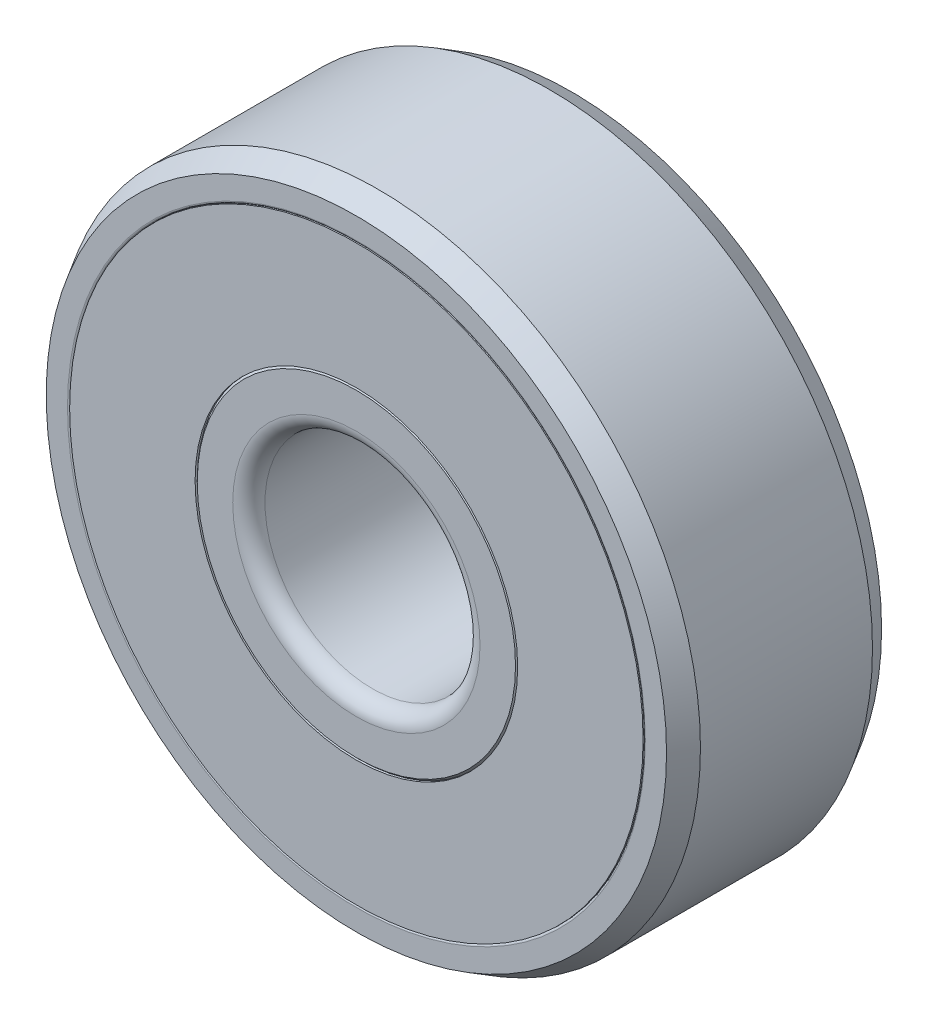
SolidWorks part; units mm, degrees
ref_plane "Front Plane" through (0, 0, 0) normal (0, 0, 1) x (1, 0, 0)
ref_plane "Top Plane" through (0, 0, 0) normal (0, 1, 0) x (1, 0, 0)
ref_plane "Right Plane" through (0, 0, 0) normal (1, 0, 0) x (0, 0, -1)
sketch "Sketch1" plane through (0, 0, 0) normal (0, 0, 1) x (1, 0, 0)
  line L0 (0, 4) -> (0, 6) construction
  line L1 (0, 2) -> (0, 4) construction
  line L2 (0, 6) -> (0, 5.3333) construction
  line L3 (0, 5.3333) -> (0, 4.6667) construction
  line L4 (0, 4.6667) -> (0, 4) construction
  circle A0 centre (0, 0) radius 2
  circle A1 centre (0, 0) radius 6
  circle A2 centre (0, 0) radius 5.3333 construction
  circle A4 centre (0, 0) radius 3 construction
  point P6 (0, 3)
  dimension "OD" = 12
  dimension "ID" = 4
sketch "Sketch2" plane through (0, 0, 0) normal (1, 0, 0) x (0, 0, -1)
  line L0 (-2, 6) -> (2, 6) construction
  line L1 (2, 6) -> (2, -6) construction
  line L2 (2, 0) -> (-2, 0) construction
  line L3 (-2, 2) -> (-2, -2) construction
  point P2 (0, 6)
  dimension "Width" = 4
  dimension "For Shaft Diameter" = 4
  dimension "For Housing ID" = 12
sketch "Sketch3" plane through (0, 0, 0) normal (1, 0, 0) x (0, 0, -1)
  line L0 (-1.6, -6) -> (1.6, -6)
  line L3 (-2, -5.3733) -> (-2, -5.7691)
  line L4 (0, -3) -> (0, -5.3333) construction
  line L5 (-1.6, -6) -> (-2, -5.7691)
  line L6 (-1.7, -2) -> (1.7, -2)
  line L7 (-1.1111, -5.3333) -> (-1.1111, -5.5556) construction
  line L8 (-1.96, -3) -> (-1.1111, -3)
  line L9 (-2, -3) -> (0, -3) construction
  line L11 (-2, -5.3333) -> (-2, -3) construction
  line L12 (-2, -2.96) -> (-2, -2.3)
  line L14 (-2, 0) -> (2, 0) construction
  line L15 (-1.96, -5.3333) -> (-1.1111, -5.3333)
  line L17 (0, 0) -> (0, -6) construction
  line L18 (-1.1111, -5.5556) -> (-1.1111, -5.7778) construction
  line L19 (1.6, -6) -> (2, -5.7691)
  line L20 (0, -5.3333) -> (-2, -5.3333) construction
  line L21 (-2, 2) -> (-2, -2) construction
  line L22 (-1.1111, -5.7778) -> (-1.1111, -6) construction
  line L30 (-2, -2.96) -> (-1.96, -3)
  line L31 (1.96, -3) -> (1.1111, -3)
  line L32 (2, -2.96) -> (1.96, -3)
  line L33 (2, -2.96) -> (2, -2.3)
  line L34 (1.96, -5.3333) -> (1.1111, -5.3333)
  line L35 (2, -5.3733) -> (2, -5.7691)
  line L36 (0, 6) -> (0, -6) construction
  arc A0 (0, -2.5556) -> (0, -5.7778) centre (0, -4.1667) ccw construction
  arc A1 (-1.1111, -3) -> (1.1111, -3) centre (0, -4.1667) cw
  arc A2 (-1.1111, -5.3333) -> (1.1111, -5.3333) centre (0, -4.1667) ccw
  arc A4 (-1.96, -5.3333) -> (-2, -5.3733) centre (-1.96, -5.3733) ccw
  arc A5 (-1.7, -2) -> (-2, -2.3) centre (-1.7, -2.3) ccw
  arc A6 (1.7, -2) -> (2, -2.3) centre (1.7, -2.3) cw
  arc A7 (1.96, -5.3333) -> (2, -5.3733) centre (1.96, -5.3733) cw
  point P28 (0, -4.1667)
  point P46 (-2, -2)
  point P54 (0, -2)
  dimension "D4" = 0.04
  dimension "D7" = 0.3
  dimension "D5" = 45
  dimension "D6" = 0.04
  dimension "D3" = 0.4
  dimension "D2" = 60
revolve "Revolve1" add sketch "Sketch3" angle 360 about L14
sketch "Sketch4" plane through (0, 0, 0) normal (1, 0, 0) x (0, 0, -1)
  line L0 (-1.96, -5.3333) -> (-1.1111, -5.3333) construction
  line L1 (-2, -3) -> (-1.7083, -3)
  line L2 (-2, -3) -> (-2, -5.3333)
  line L3 (-2, -5.3333) -> (-1.7083, -5.3333)
  line L4 (-1.7083, -3) -> (-1.7083, -5.3333)
  line L5 (-2, -2.96) -> (-2, -2.3) construction
  line L6 (-2, -4.1667) -> (-1.9028, -4.1667) construction
  line L7 (-1.9028, -4.1667) -> (-1.8056, -4.1667) construction
  line L8 (-1.8056, -4.1667) -> (-1.7083, -4.1667) construction
  line L9 (-1.7083, -4.1667) -> (-1.6111, -4.1667) construction
  line L10 (-2, -5.3333) -> (-2, -3) construction
  line L11 (-1.96, -3) -> (-1.1111, -3) construction
  arc A1 (0, -2.5556) -> (0, -5.7778) centre (0, -4.1667) ccw construction
revolve "Revolve2" add sketch "Sketch4" angle 360 about L14
sketch "Sketch5" plane through (0, 0, 0) normal (1, 0, 0) x (0, 0, -1)
  line L2 (0, -2.5556) -> (0, -5.7778)
  arc A2 (0, -5.7778) -> (0, -2.5556) centre (0, -4.1667) cw
revolve "Revolve3" add sketch "Sketch5" angle 360 about L17
pattern_circular "CirPattern1" count 7 over 360 about axis through (0, 0, 0) along (0, 0, 1) of bodies 138
equation "\"D4@Sketch3\"=\"Width@Sketch2\"*.01"
equation "\"D6@Sketch3\"=\"Width@Sketch2\"*.01"
equation "\"D7@Sketch3\"=\"Width@Sketch2\"*.075"
equation "\"D3@Sketch3\"=\"Width@Sketch2\"*.1"
